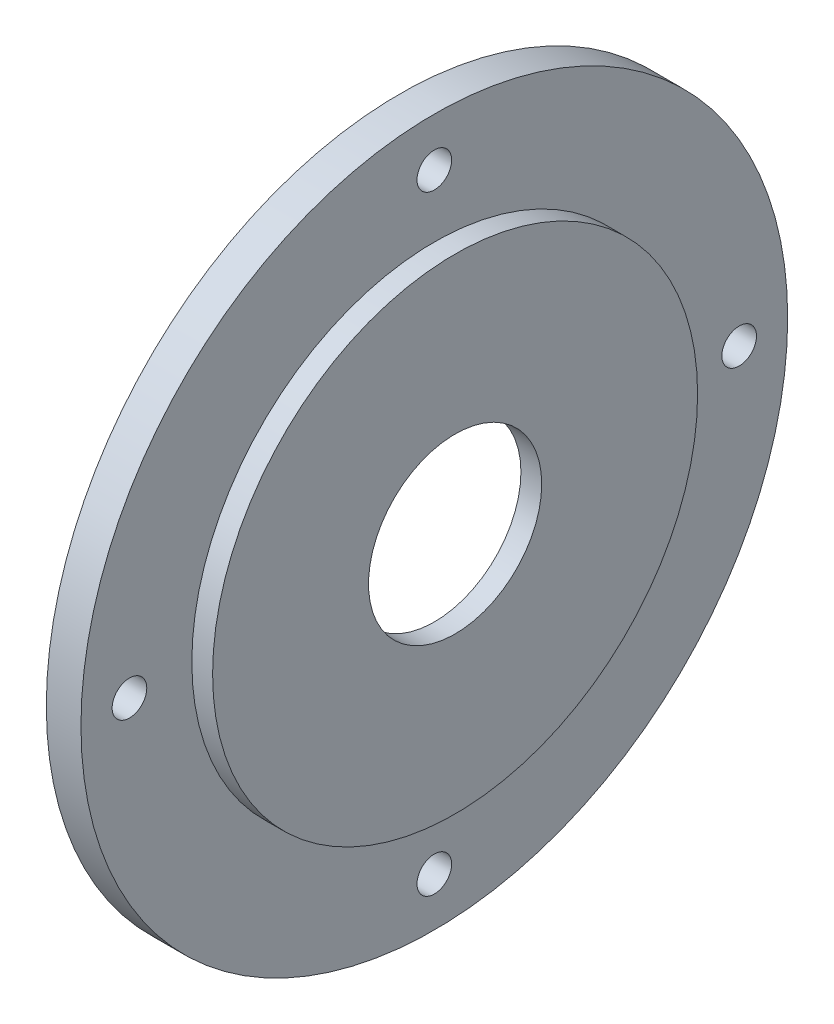
SolidWorks part; units mm, degrees
ref_plane "前视基准面" through (0, 0, 0) normal (0, 0, 1) x (1, 0, 0)
ref_plane "上视基准面" through (0, 0, 0) normal (0, 1, 0) x (1, 0, 0)
ref_plane "右视基准面" through (0, 0, 0) normal (1, 0, 0) x (0, 0, -1)
sketch "草图1" plane through (0, 0, 0) normal (1, 0, 0) x (0, 0, -1)
  circle A0 centre (0, 0) radius 27
  circle A1 centre (0, 0) radius 51
extrude "凸台-拉伸1" add sketch "草图1" along normal blind 5
sketch "草图2" plane through (5, 0, 0) normal (1, 0, 0) x (0, 0, -1)
  circle A0 centre (0, 0) radius 35
extrude "凸台-拉伸2" add sketch "草图2" along normal blind 3
sketch "草图3" plane through (5, 0, 0) normal (1, 0, 0) x (0, 0, -1)
  circle A0 centre (0, 44) radius 2.5
  circle A1 centre (44, 0) radius 2.5
  circle A2 centre (0, -44) radius 2.5
  circle A3 centre (-44, 0) radius 2.5
  point P11 (0, 0)
  dimension "D1" = 4
extrude "切除-拉伸1" cut sketch "草图3" against normal up to surface (5 mm away) up to face at (0, 0, -51)
sketch "草图4" plane through (8, 0, 0) normal (1, 0, 0) x (0, 0, -1)
  circle A0 centre (0, 0) radius 12.5
extrude "切除-拉伸2" cut sketch "草图4" against normal up to surface (8 mm away) up to face at (0, 44, -2.5)
